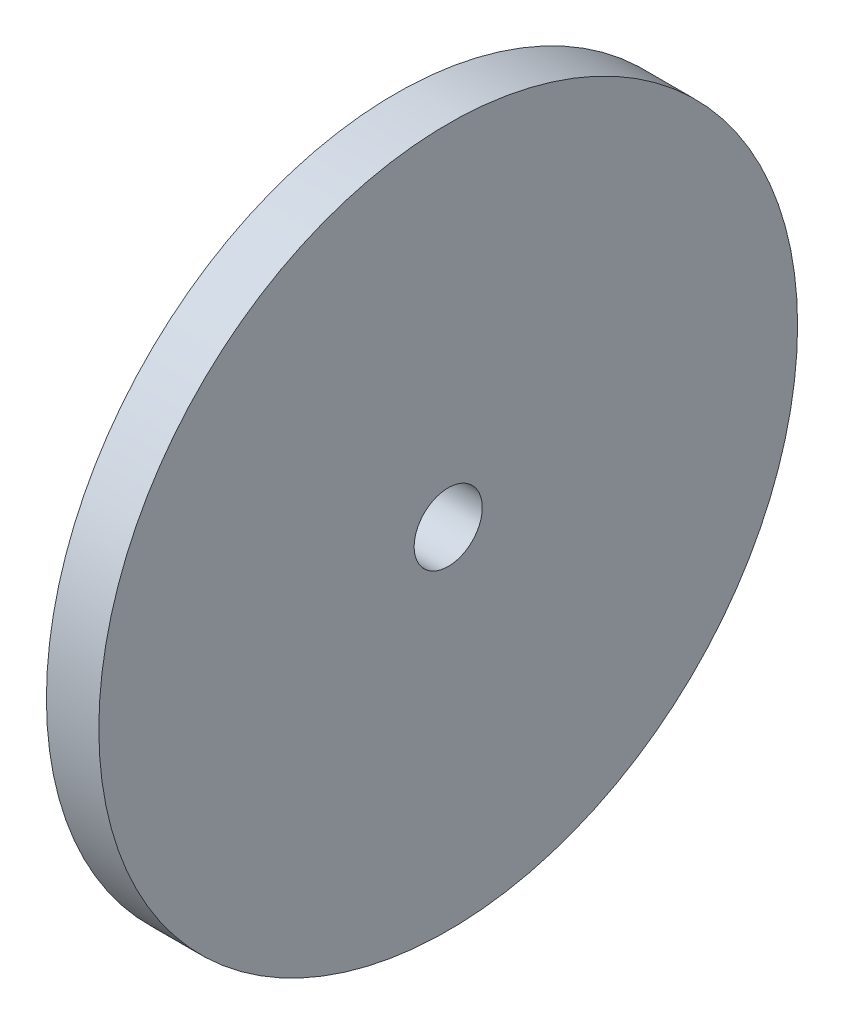
SolidWorks part; units mm, degrees
ref_plane "Front Plane" through (0, 0, 0) normal (0, 0, 1) x (1, 0, 0)
ref_plane "Top Plane" through (0, 0, 0) normal (0, 1, 0) x (1, 0, 0)
ref_plane "Right Plane" through (0, 0, 0) normal (1, 0, 0) x (0, 0, -1)
sketch "Sketch1" plane through (0, 0, 0) normal (0, 0, 1) x (1, 0, 0)
  line L1 (-0.75, 10) -> (0.75, 10) construction
  line L2 (-0.75, 10) -> (-0.75, 0) construction
  line L3 (-0.75, 0) -> (0.75, 0) construction
  line L4 (0.75, 10) -> (0.75, 0) construction
  line L5 (-0.75, 0.975) -> (0.75, 0.975)
  line L6 (-0.75, 0.975) -> (-0.75, 10)
  line L8 (0.75, 0.975) -> (0.75, 10)
  line L10 (-0.75, 10) -> (0.75, 10)
  point P0 (-0.713, 10)
  dimension "D2" = 1.5
  dimension "D3" = 0.975
  dimension "D4" = 10
revolve "Revolve1" add sketch "Sketch1" angle 360 about L3
